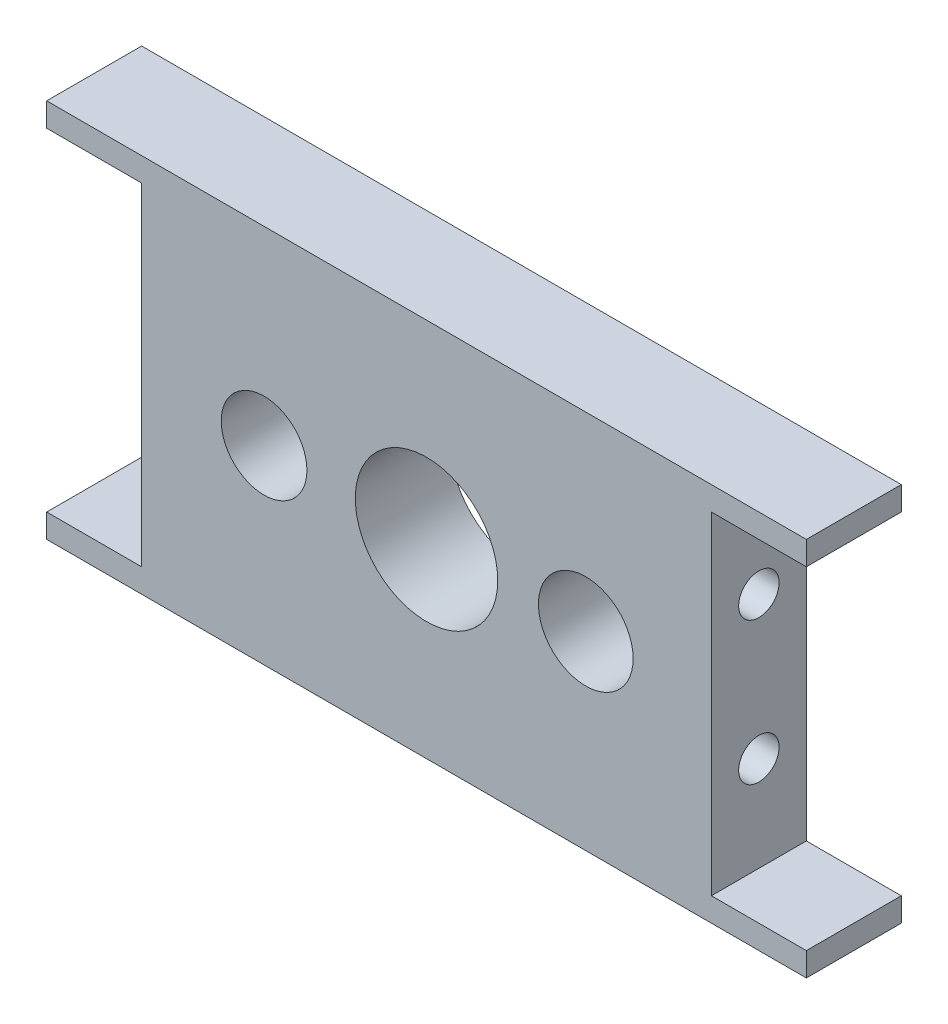
SolidWorks part; units mm, degrees
material "6061-T6 (SS)"
ref_plane "Front Plane" through (0, 0, 0) normal (0, 0, 1) x (1, 0, 0)
ref_plane "Top Plane" through (0, 0, 0) normal (0, 1, 0) x (1, 0, 0)
ref_plane "Right Plane" through (0, 0, 0) normal (1, 0, 0) x (0, 0, -1)
sketch "Sketch1" plane through (0, 0, 0) normal (0, 0, 1) x (1, 0, 0)
  line L0 (25.4, -11.1125) -> (25.4, -12.7)
  line L1 (25.4, 12.7) -> (-25.4, 12.7)
  line L2 (25.4, 12.7) -> (25.4, 11.1125)
  line L3 (25.4, -12.7) -> (-25.4, -12.7)
  line L4 (-25.4, 12.7) -> (-25.4, 11.1125)
  line L5 (25.4, 11.1125) -> (19.05, 11.1125)
  line L6 (-25.4, -11.1125) -> (-25.4, -12.7)
  line L7 (25.4, -11.1125) -> (19.05, -11.1125)
  line L8 (19.05, 11.1125) -> (19.05, -11.1125)
  line L9 (-25.4, 11.1125) -> (-19.05, 11.1125)
  line L11 (-25.4, -11.1125) -> (-19.05, -11.1125)
  line L12 (-19.05, 11.1125) -> (-19.05, -11.1125)
  circle A0 centre (0, 0) radius 4.7625
  circle A1 centre (-10.8631, 0) radius 2.8656
  circle A2 centre (10.6501, 0) radius 3.1665
  dimension "D1" = 9.525
  dimension "D2" = 25.4
  dimension "D3" = 25.4
  dimension "D4" = 6.35
  dimension "D5" = 1.5875
  dimension "D6" = 1.5875
  dimension "D7" = 50.8
  dimension "D8" = 1.5875
  dimension "D9" = 1.5875
  dimension "D10" = 6.35
  dimension "D11" = 12.7
extrude "Boss-Extrude1" add sketch "Sketch1" along normal blind 6.35
hole_wizard "Tap Drill for #6-32 Tap1" positions "Sketch3" profile "Sketch4" hole size "#6-32" standard "ANSI Inch"
sketch "Sketch3" plane through (19.05, 0, 0) normal (1, 0, 0) x (0, 0, -1)
  point P0 (-3.175, 4.7625)
  point P3 (-3.175, -4.7625)
sketch "Sketch4" plane through (19.05, 4.7625, 3.175) normal (0, 1, 0) x (0, 0, -1)
  line L0 (0, 0) -> (0, 7.1627)
  line L1 (0, 7.1627) -> (1.3525, 6.35)
  line L2 (1.3525, 6.35) -> (1.3525, 0)
  line L5 (1.3525, 0) -> (0, 0)
  line L10 (0, 7.1627) -> (-1.3526, 6.35) construction
  line L11 (0, -6.35) -> (0, 107.95) construction
  dimension "Hole Dia." = 2.7051
  dimension "Hole Depth" = 6.35
  dimension "Drill Angle" = 118
ref_plane "Plane1" through (0, 0, 0) normal (-1, 0, 0) x (0, 0, 1)
mirror "Mirror1" about plane through (0, 0, 0) normal (-1, 0, 0) of "Tap Drill for #6-32 Tap1"
